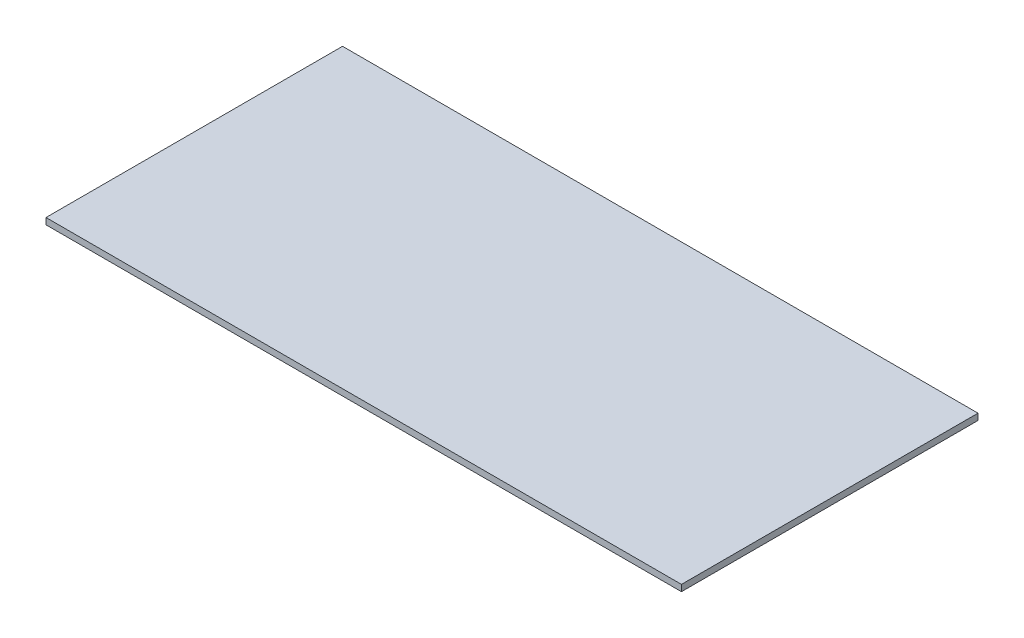
SolidWorks part; units mm, degrees
material "Arce"
ref_plane "Alzado" through (0, 0, 0) normal (0, 0, 1) x (1, 0, 0)
ref_plane "Planta" through (0, 0, 0) normal (0, 1, 0) x (1, 0, 0)
ref_plane "Vista lateral" through (0, 0, 0) normal (1, 0, 0) x (0, 0, -1)
sketch "Croquis2" plane through (0, 0, 0) normal (0, 1, 0) x (1, 0, 0)
  line L1 (-300, 140) -> (300, 140)
  line L2 (-300, 140) -> (-300, -140)
  line L3 (-300, -140) -> (300, -140)
  line L4 (300, 140) -> (300, -140)
  line L5 (-300, 140) -> (300, -140) construction
  line L6 (-300, -140) -> (300, 140) construction
  point P0 (0, 0)
  dimension "D1" = 600
  dimension "D2" = 280
extrude "Saliente-Extruir1" add sketch "Croquis2" along normal blind 6
